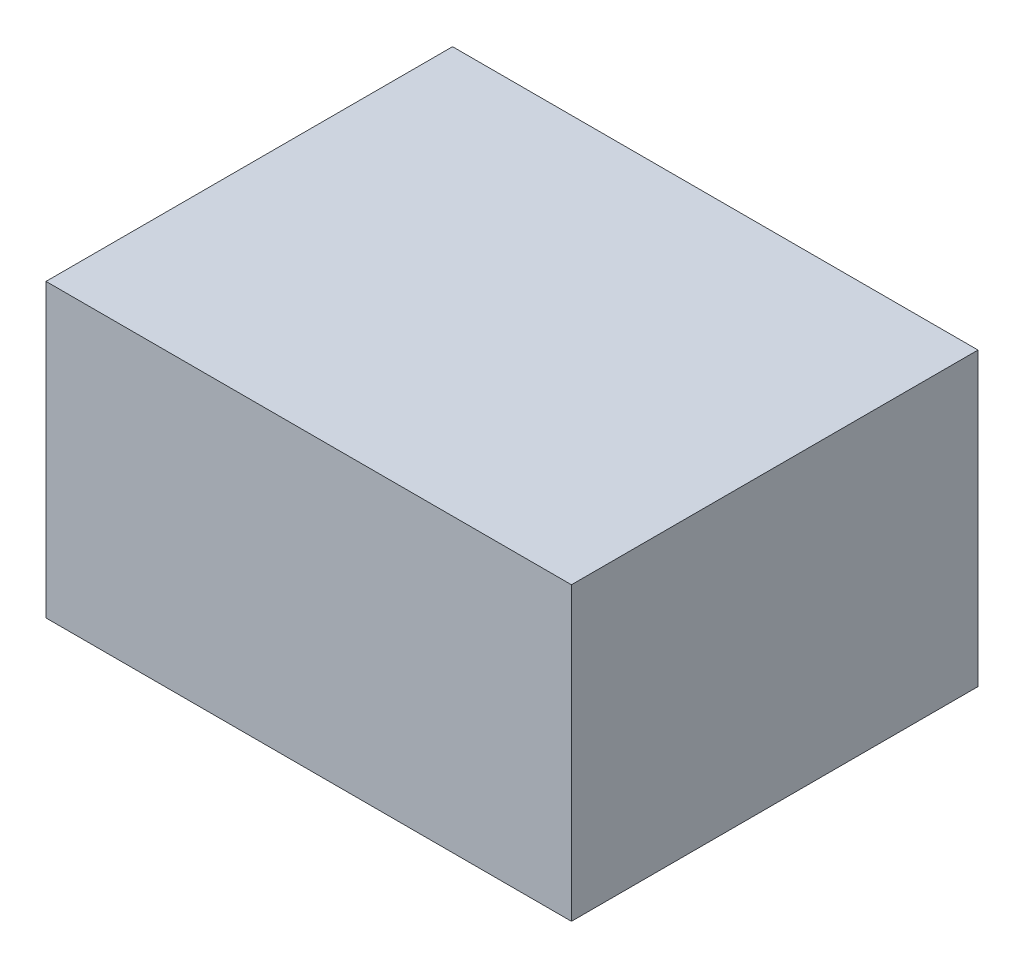
SolidWorks part; units mm, degrees
ref_plane "Front Plane" through (0, 0, 0) normal (0, 0, 1) x (1, 0, 0)
ref_plane "Top Plane" through (0, 0, 0) normal (0, 1, 0) x (1, 0, 0)
ref_plane "Right Plane" through (0, 0, 0) normal (1, 0, 0) x (0, 0, -1)
sketch "Sketch1" plane through (0, 0, 0) normal (0, 1, 0) x (1, 0, 0)
  line L1 (-34.25, -26.5) -> (34.25, -26.5)
  line L2 (-34.25, -26.5) -> (-34.25, 26.5)
  line L3 (-34.25, 26.5) -> (34.25, 26.5)
  line L4 (34.25, -26.5) -> (34.25, 26.5)
  line L5 (-34.25, -26.5) -> (34.25, 26.5) construction
  line L6 (-34.25, 26.5) -> (34.25, -26.5) construction
  point P0 (0, 0)
  dimension "D1" = 68.5
  dimension "D2" = 53
extrude "Boss-Extrude1" add sketch "Sketch1" along normal blind 38
